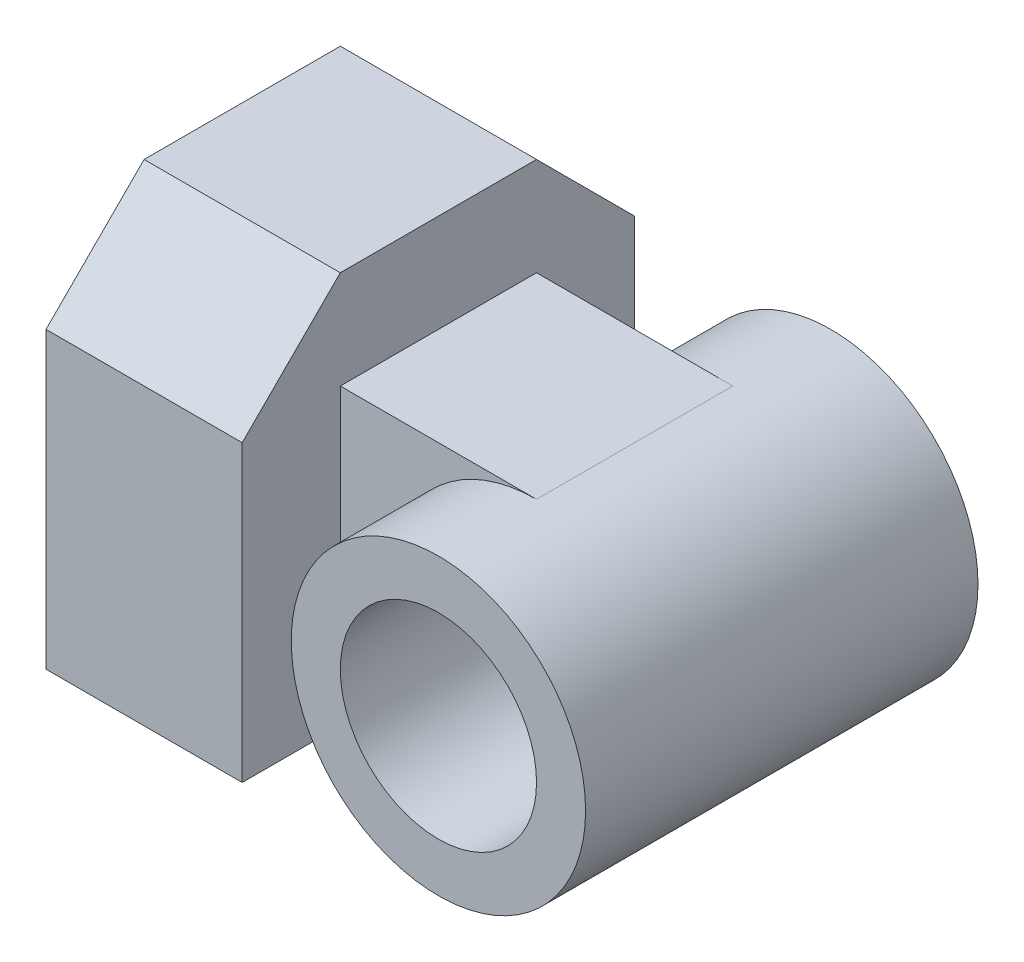
SolidWorks part; units mm, degrees
ref_plane "Front Plane" through (0, 0, 0) normal (0, 0, 1) x (1, 0, 0)
ref_plane "Top Plane" through (0, 0, 0) normal (0, 1, 0) x (1, 0, 0)
ref_plane "Right Plane" through (0, 0, 0) normal (1, 0, 0) x (0, 0, -1)
sketch "Sketch2" plane through (0, 0, 0) normal (0, 0, 1) x (1, 0, 0)
  line L1 (-25.4, -50.8) -> (25.4, -50.8)
  line L2 (-25.4, -50.8) -> (-25.4, 50.8)
  line L3 (-25.4, 50.8) -> (25.4, 50.8)
  line L4 (25.4, -50.8) -> (25.4, 50.8)
  line L5 (-25.4, -50.8) -> (25.4, 50.8) construction
  line L6 (-25.4, 50.8) -> (25.4, -50.8) construction
  point P0 (0, 0)
  dimension "D1" = 50.8
  dimension "D2" = 101.6
extrude "Boss-Extrude1" add sketch "Sketch2" along normal mid plane 101.6
ref_plane "Plane1" through (76.2, 0, 0) normal (1, 0, 0) x (0, 0, -1)
sketch "Sketch3" plane through (76.2, 0, 0) normal (1, 0, 0) x (0, 0, -1)
  line L0 (-50.8, -50.8) -> (50.8, -50.8) construction
  line L1 (-25.4, -50.8) -> (25.4, -50.8)
  line L2 (-25.4, -50.8) -> (-25.4, 25.4)
  line L3 (-25.4, 25.4) -> (25.4, 25.4)
  line L4 (25.4, -50.8) -> (25.4, 25.4)
  line L5 (-25.4, -50.8) -> (25.4, 25.4) construction
  line L6 (-25.4, 25.4) -> (25.4, -50.8) construction
  line L7 (-50.8, -50.8) -> (-50.8, 50.8) construction
  line L8 (-50.8, 50.8) -> (50.8, 50.8) construction
  line L9 (50.8, -50.8) -> (50.8, 50.8) construction
  point P4 (0, -12.7)
  dimension "D1" = 25.4
  dimension "D2" = 25.4
  dimension "D3" = 25.4
extrude "Boss-Extrude2" add sketch "Sketch3" against normal up to surface (50.8 mm away) up to face at (25.4, 0, 0)
ref_plane "Plane2" through (0, 0, 50.8) normal (0, 0, 1) x (1, 0, 0)
sketch "Sketch4" plane through (0, 0, 50.8) normal (0, 0, 1) x (1, 0, 0)
  line L0 (76.2, 25.4) -> (76.2, -50.8) construction
  circle A0 centre (76.2, -12.7) radius 38.1
extrude "Boss-Extrude3" add sketch "Sketch4" against normal up to surface (101.6 mm away) up to face at (0, 0, -50.8)
chamfer "Chamfer2" distance 25.4 2 edges at (0, 50.8, -50.8) (0, 50.8, 50.8)
hole_wizard "Hole1" positions "3DSketch1" profile "Sketch5" legacy end condition through all
sketch3d "3DSketch1"
  line L0 (76.2, -12.7, -50.8) -> (76.2, -12.7, 50.8) construction
  point P0 (76.2, -12.7, 50.8)
sketch "Sketch5" plane through (76.2, -12.7, 50.8) normal (1, 0, 0) x (0, -1, 0)
  line L0 (0, 0) -> (0, 101.6)
  line L1 (0, 101.6) -> (25.4, 101.6)
  line L2 (25.4, 101.6) -> (25.4, 0)
  line L3 (25.4, 0) -> (0, 0)
  line L4 (0, 110) -> (0, -10) construction
  dimension "Diameter" = 50.8
  dimension "Depth" = 101.6
